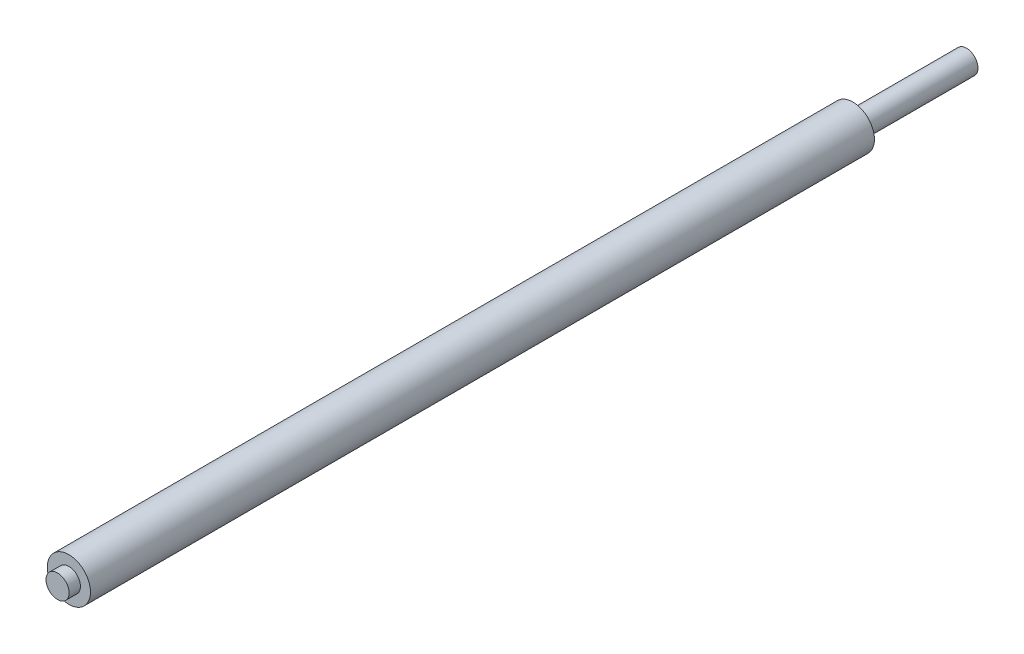
SolidWorks part; units mm, degrees
ref_plane "前视基准面" through (0, 0, 0) normal (0, 0, 1) x (1, 0, 0)
ref_plane "上视基准面" through (0, 0, 0) normal (0, 1, 0) x (1, 0, 0)
ref_plane "右视基准面" through (0, 0, 0) normal (1, 0, 0) x (0, 0, -1)
sketch "草图1" plane through (0, 0, 0) normal (0, 0, 1) x (1, 0, 0)
  circle A0 centre (0, 0) radius 0.1016
  dimension "D1" = 0.2032
extrude "凸台-拉伸1" add sketch "草图1" along normal mid plane 8
sketch "草图2" plane through (0, 0, 0) normal (0, 0, 1) x (1, 0, 0)
  circle A0 centre (0, 0.0011) radius 0.19
  dimension "D1" = 0.38
extrude "凸台-拉伸2" add sketch "草图2" along normal blind 3.9 and the other way blind 3
